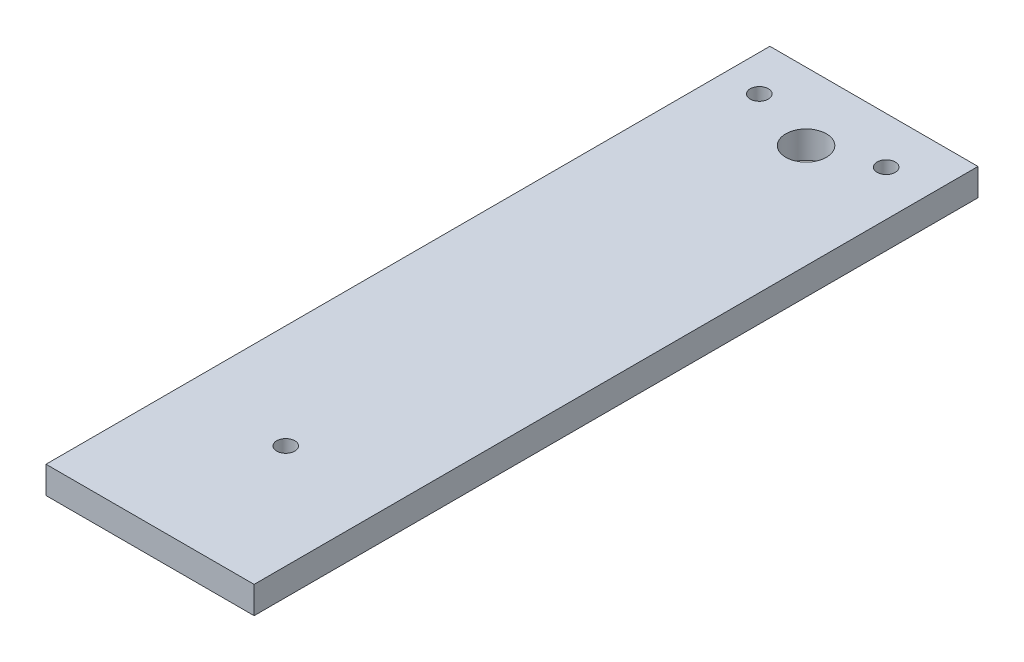
SolidWorks part; units mm, degrees
ref_plane "Plan de face" through (0, 0, 0) normal (0, 0, 1) x (1, 0, 0)
ref_plane "Plan de dessus" through (0, 0, 0) normal (0, 1, 0) x (1, 0, 0)
ref_plane "Plan de droite" through (0, 0, 0) normal (1, 0, 0) x (0, 0, -1)
sketch "Esquisse1" plane through (0, 0, 0) normal (0, 0, 1) x (1, 0, 0)
  line L1 (11.5, 1.5) -> (-11.5, 1.5)
  line L2 (11.5, 1.5) -> (11.5, -1.5)
  line L3 (11.5, -1.5) -> (-11.5, -1.5)
  line L4 (-11.5, 1.5) -> (-11.5, -1.5)
  line L5 (11.5, 1.5) -> (-11.5, -1.5) construction
  line L6 (11.5, -1.5) -> (-11.5, 1.5) construction
  point P0 (0, 0)
  dimension "D1" = 23
  dimension "D2" = 3
extrude "Boss.-Extru.1" add sketch "Esquisse1" along normal blind 80
sketch "Esquisse2" plane through (0, 1.5, 0) normal (0, 1, 0) x (1, 0, 0)
  circle A0 centre (11.1349, -5.3686) radius 1.845
  circle A1 centre (-10.1071, -5.3686) radius 1.7131
sketch "Esquisse3" plane through (0, -1.5, 0) normal (0, -1, 0) x (1, 0, 0)
  line L0 (-11.5, 0) -> (11.5, 0) construction
  circle A1 centre (0, 65) radius 1
  dimension "D2" = 2
  dimension "D1" = 65
extrude "Enlèv. mat.-Extru.2" cut sketch "Esquisse3" against normal blind 10
sketch "Esquisse4" plane through (0, -1.5, 0) normal (0, -1, 0) x (-1, 0, 0)
  circle A0 centre (-6.4973, -5.1442) radius 1
  circle A1 centre (7.5248, -5.1442) radius 1
  dimension "D1" = 2
  dimension "D2" = 2
extrude "Enlèv. mat.-Extru.3" cut sketch "Esquisse4" against normal blind 10
sketch "Esquisse5" plane through (0, 1.5, 0) normal (0, 1, 0) x (1, 0, 0)
  circle A0 centre (0, -7.5) radius 2.25
extrude "Enlèv. mat.-Extru.4" cut sketch "Esquisse5" against normal through all
